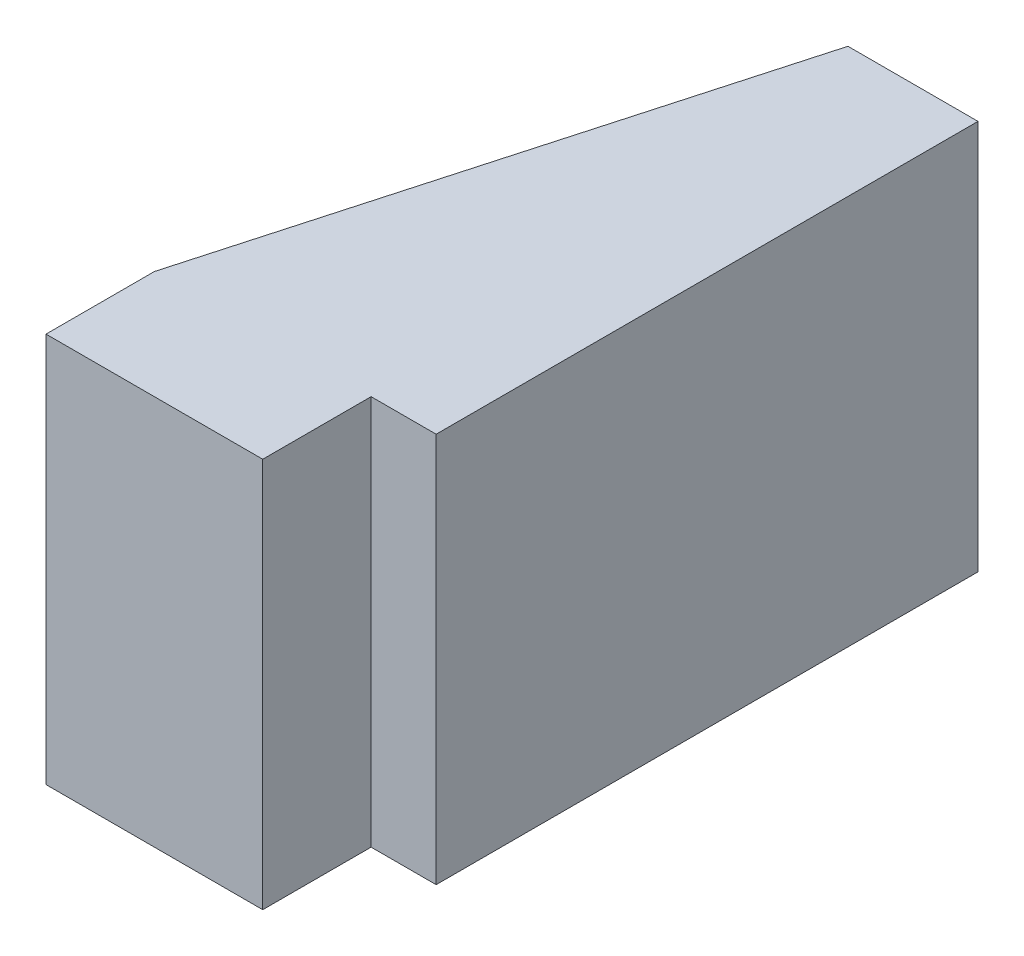
SolidWorks part; units mm, degrees
ref_plane "Plan de face" through (0, 0, 0) normal (0, 0, 1) x (1, 0, 0)
ref_plane "Plan de dessus" through (0, 0, 0) normal (0, 1, 0) x (1, 0, 0)
ref_plane "Plan de droite" through (0, 0, 0) normal (1, 0, 0) x (0, 0, -1)
sketch "Esquisse1" plane through (0, 0, 0) normal (0, 1, 0) x (1, 0, 0)
  line L0 (6.8735, 12.2076) -> (3.8735, 12.2076)
  line L1 (3.8735, 12.2076) -> (6.8735, 12.2076)
  line L2 (-3.1265, -12.7924) -> (-3.1265, -17.7924)
  line L3 (-3.1265, -17.7924) -> (6.8735, -17.7924)
  line L4 (6.8735, -12.7924) -> (6.8735, -17.7924)
  line L5 (-3.1265, -17.7924) -> (-3.1265, -12.7924)
  line L6 (3.8735, 12.2076) -> (-3.1265, -12.7924)
  line L8 (6.8735, 12.2076) -> (9.8735, 12.2076)
  line L10 (6.8735, -12.7924) -> (9.8735, -12.7924)
  line L11 (9.8735, 12.2076) -> (9.8735, -12.7924)
  dimension "D1" = 30
  dimension "D2" = 3
  dimension "D3" = 3
  dimension "D4" = 5
  dimension "D5" = 25
extrude "Boss.-Extru.1" add sketch "Esquisse1" along normal blind 18 contours L11 L8 L0 L6 L2 L3 L4 L10
